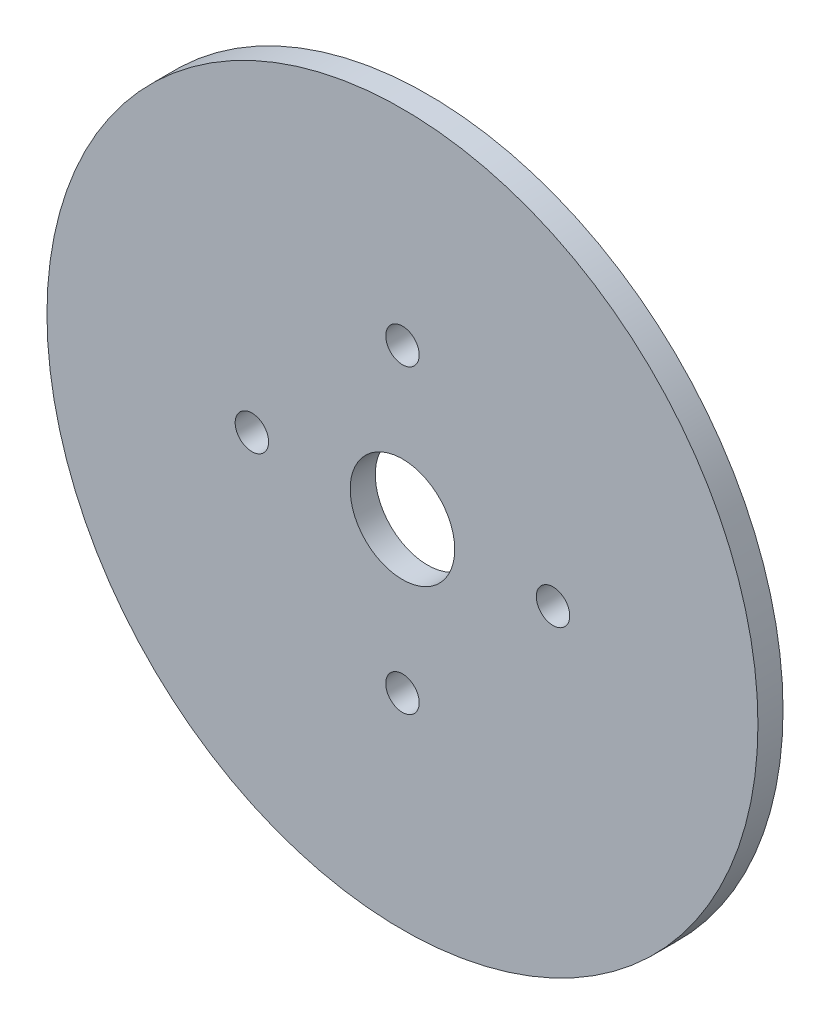
SolidWorks part; units mm, degrees
ref_plane "Front Plane" through (0, 0, 0) normal (0, 0, 1) x (1, 0, 0)
ref_plane "Top Plane" through (0, 0, 0) normal (0, 1, 0) x (1, 0, 0)
ref_plane "Right Plane" through (0, 0, 0) normal (1, 0, 0) x (0, 0, -1)
sketch "Sketch1" plane through (0, 0, 0) normal (0, 0, 1) x (1, 0, 0)
  circle A0 centre (0, 0) radius 12.5
  circle A1 centre (0, 0) radius 85
extrude "Boss-Extrude1" add sketch "Sketch1" along normal blind 6
sketch "Sketch2" plane through (0, 0, 6) normal (0, 0, 1) x (1, 0, 0)
  circle A0 centre (0, 36) radius 4
  circle A1 centre (36, 0) radius 4
  circle A2 centre (0, -36) radius 4
  circle A3 centre (-36, 0) radius 4
  point P12 (0, 0)
  dimension "D1" = 36
  dimension "D2" = 4
extrude "Cut-Extrude1" cut sketch "Sketch2" against normal through all
